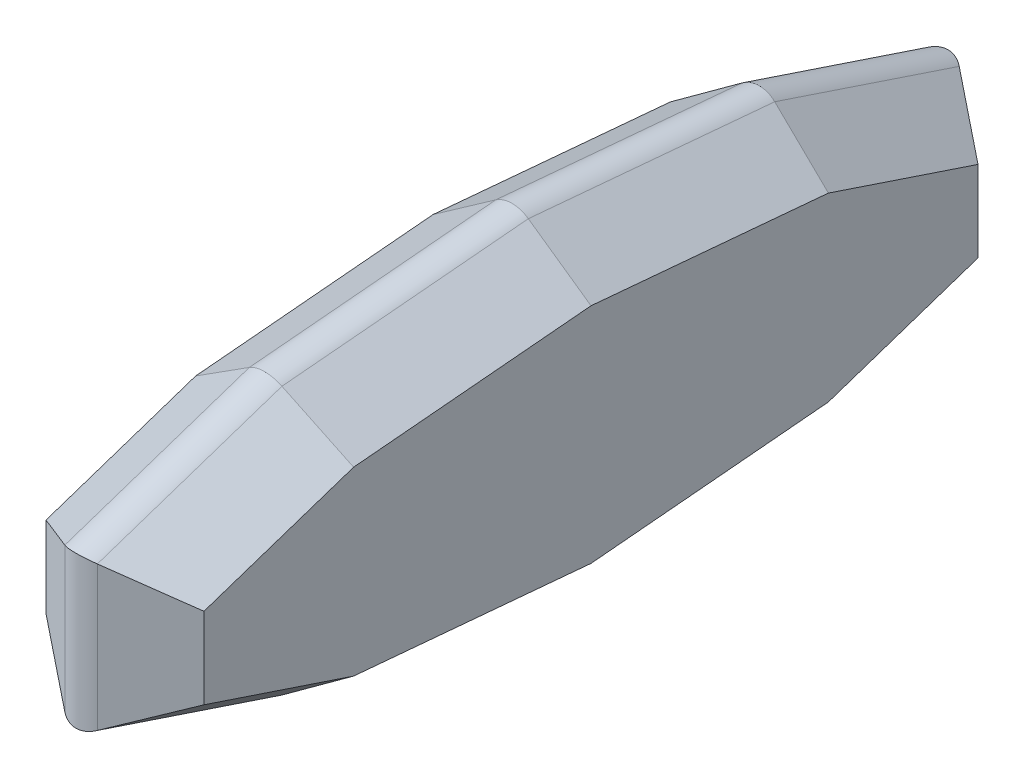
SolidWorks part; units mm, degrees
ref_plane "Front Plane" through (0, 0, 0) normal (0, 0, 1) x (1, 0, 0)
ref_plane "Top Plane" through (0, 0, 0) normal (0, 1, 0) x (1, 0, 0)
ref_plane "Right Plane" through (0, 0, 0) normal (1, 0, 0) x (0, 0, -1)
sketch "Sketch2" plane through (0, 0, 0) normal (1, 0, 0) x (0, 0, -1)
  line L0 (-355.6, 0) -> (355.6, 0) construction
  line L1 (-355.6, -64.5789) -> (-355.6, 64.5789)
  line L2 (-355.6, 64.5789) -> (-199.9701, 116.5527)
  line L3 (0, 400.3801) -> (0, -400.3801) construction
  line L4 (-199.9701, 116.5527) -> (0, 134.3337)
  line L5 (-199.9701, -116.5527) -> (0, -134.3337)
  line L6 (-355.6, -64.5789) -> (-199.9701, -116.5527)
  line L7 (199.9701, -116.5527) -> (0, -134.3337)
  line L8 (355.6, -64.5789) -> (199.9701, -116.5527)
  line L9 (355.6, -64.5789) -> (355.6, 64.5789)
  line L10 (355.6, 64.5789) -> (199.9701, 116.5527)
  line L11 (199.9701, 116.5527) -> (0, 134.3337)
  point P4 (0, 0)
  point P9 (0, 0)
  dimension "D1" = 711.2
extrude "Boss-Extrude1" add sketch "Sketch2" along normal blind 63.5 draft 35
sketch "Sketch3" plane through (0, 0, 0) normal (-1, 0, 0) x (0, 0, 1)
  line L10 (0, 134.3337) -> (-199.9701, 116.5527)
  line L11 (-199.9701, 116.5527) -> (-355.6, 64.5789)
  line L12 (-355.6, 64.5789) -> (-355.6, -64.5789)
  line L13 (-355.6, -64.5789) -> (-199.9701, -116.5527)
  line L14 (-199.9701, -116.5527) -> (0, -134.3337)
  line L15 (0, -134.3337) -> (199.9701, -116.5527)
  line L16 (199.9701, -116.5527) -> (355.6, -64.5789)
  line L17 (355.6, -64.5789) -> (355.6, 64.5789)
  line L18 (355.6, 64.5789) -> (199.9701, 116.5527)
  line L19 (199.9701, 116.5527) -> (0, 134.3337)
  line L20 (0, 134.3337) -> (-199.9701, 116.5527)
  line L21 (-199.9701, 116.5527) -> (-355.6, 64.5789)
  line L22 (-355.6, 64.5789) -> (-355.6, -64.5789)
  line L23 (-355.6, -64.5789) -> (-199.9701, -116.5527)
  line L24 (-199.9701, -116.5527) -> (0, -134.3337)
  line L25 (0, -134.3337) -> (199.9701, -116.5527)
  line L26 (199.9701, -116.5527) -> (355.6, -64.5789)
  line L27 (355.6, -64.5789) -> (355.6, 64.5789)
  line L28 (355.6, 64.5789) -> (199.9701, 116.5527)
  line L29 (199.9701, 116.5527) -> (0, 134.3337)
  dimension "D1" = 0
extrude "Boss-Extrude2" add sketch "Sketch3" along normal blind 63.5 draft 35
fillet "Fillet1" radius 22.86 10 edges at (0, 0, 355.6) (0, 90.5658, 277.785) (0, 125.4432, 99.985) (0, 125.4432, -99.985) (0, 90.5658, -277.785) (0, 0, -355.6) (0, -90.5658, -277.785) (0, -125.4432, -99.985) (0, -125.4432, 99.985) (0, -90.5658, 277.785)
